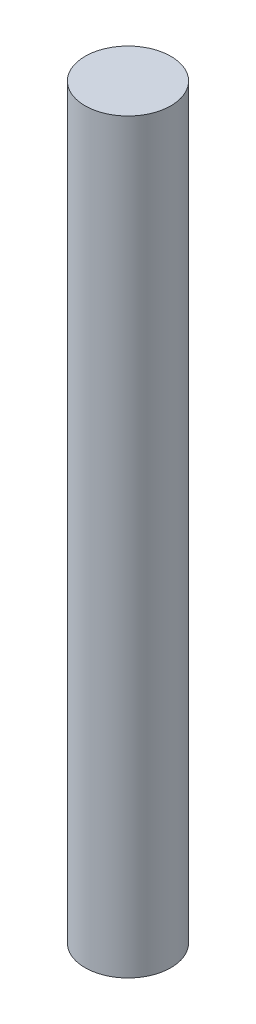
SolidWorks part; units mm, degrees
ref_plane "Front Plane" through (0, 0, 0) normal (0, 0, 1) x (1, 0, 0)
ref_plane "Top Plane" through (0, 0, 0) normal (0, 1, 0) x (1, 0, 0)
ref_plane "Right Plane" through (0, 0, 0) normal (1, 0, 0) x (0, 0, -1)
sketch "Sketch1" plane through (0, 0, 0) normal (0, 1, 0) x (1, 0, 0)
  circle A0 centre (0, 0) radius 5
  dimension "D1" = 10
extrude "Boss-Extrude1" add sketch "Sketch1" along normal blind 87
